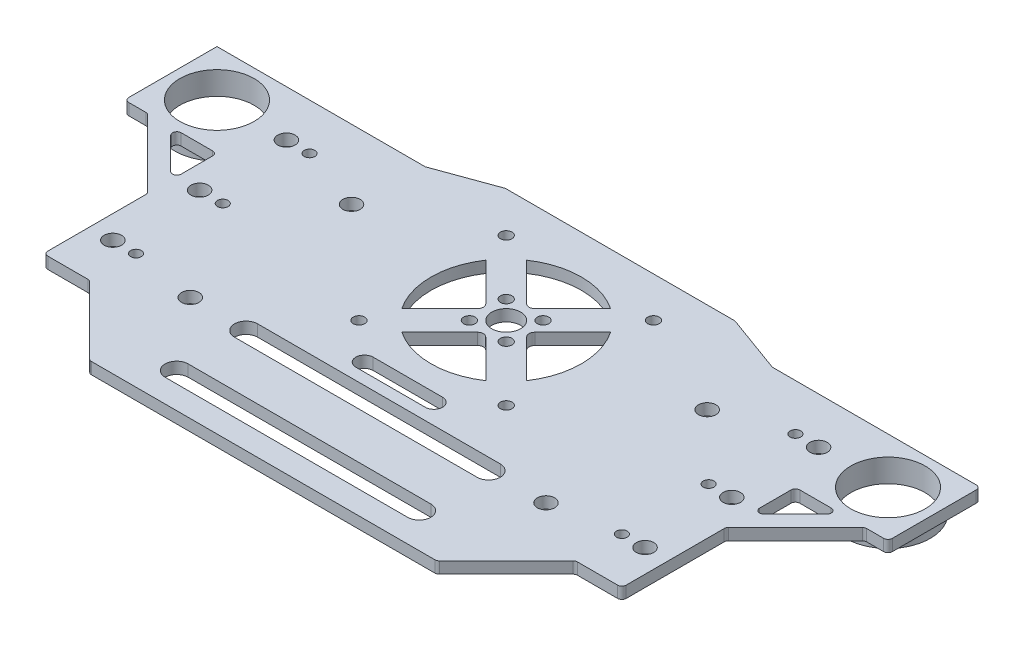
SolidWorks part; units mm, degrees
ref_plane "前视基准面" through (0, 0, 0) normal (0, 0, 1) x (1, 0, 0)
ref_plane "上视基准面" through (0, 0, 0) normal (0, 1, 0) x (1, 0, 0)
ref_plane "右视基准面" through (0, 0, 0) normal (1, 0, 0) x (0, 0, -1)
other "Configuration Table"
sketch "草图1" plane through (0, 0, 0) normal (0, 1, 0) x (1, 0, 0)
  line L0 (-50, 23) -> (50, 23)
  line L1 (50, 23) -> (50, -23)
  line L2 (50, -23) -> (-50, -23)
  line L3 (-50, -23) -> (-50, 23)
  line L5 (0, 23) -> (0, -23) construction
  line L6 (3.182, 10.182) -> (-3.182, 3.818) construction
  line L7 (7.253, 17.7886) -> (-10.7886, -0.253) construction
  line L8 (10.7886, 14.253) -> (-7.253, -3.7886) construction
  line L9 (10.7886, -0.253) -> (-7.253, 17.7886) construction
  line L10 (7.253, -3.7886) -> (-10.7886, 14.253) construction
  line L11 (-7.253, -3.7886) -> (10.7886, 14.253) construction
  line L12 (-10.7886, -0.253) -> (7.253, 17.7886) construction
  line L13 (-10.7886, 14.253) -> (7.253, -3.7886) construction
  line L14 (-7.253, 17.7886) -> (10.7886, -0.253) construction
  line L15 (10.7886, -0.253) -> (4.2426, 6.2929)
  line L16 (4.2426, 7.7071) -> (10.7886, 14.253)
  line L17 (7.253, 17.7886) -> (0.7071, 11.2426)
  line L18 (-0.7071, 11.2426) -> (-7.253, 17.7886)
  line L19 (-10.7886, 14.253) -> (-4.2426, 7.7071)
  line L20 (-4.2426, 6.2929) -> (-10.7886, -0.253)
  line L21 (-7.253, -3.7886) -> (-0.7071, 2.7574)
  line L22 (0.7071, 2.7574) -> (7.253, -3.7886)
  line L23 (-30, 23) -> (-19.848, 26.695)
  line L24 (-19.848, 26.695) -> (0, 26.695)
  line L25 (30, 23) -> (19.848, 26.695)
  line L26 (19.848, 26.695) -> (0, 26.695)
  line L27 (-50, 23) -> (-66, 23)
  line L28 (-66, 23) -> (-66, 7)
  line L29 (-66, 7) -> (-50, 7)
  line L30 (-50, 7) -> (-50, 23)
  line L31 (-58, 7) -> (-50, -1)
  line L32 (-62, 7) -> (-50, -5)
  line L33 (-50, -1) -> (-50, -5)
  line L34 (-58, 7) -> (-62, 7)
  line L35 (58, 7) -> (62, 7)
  line L36 (50, -1) -> (50, -5)
  line L37 (62, 7) -> (50, -5)
  line L38 (58, 7) -> (50, -1)
  line L39 (50, 7) -> (50, 23)
  line L40 (66, 7) -> (50, 7)
  line L41 (66, 23) -> (66, 7)
  line L42 (50, 23) -> (66, 23)
  line L43 (-42, -23) -> (-30, -35)
  line L44 (-30, -35) -> (30, -35)
  line L45 (42, -23) -> (30, -35)
  line L46 (-42, -23) -> (42, -23)
  line L47 (-46, 23) -> (-46, -23) construction
  line L48 (-50, 0) -> (50, 0) construction
  line L49 (-6, -11.5) -> (6, -11.5) construction
  line L50 (-6, -10) -> (6, -10)
  line L51 (-20.9696, -17) -> (20.9696, -17) construction
  line L52 (-20.9696, -15) -> (20.9696, -15)
  line L53 (-20.9696, -19) -> (20.9696, -19)
  line L54 (-20.9696, -29) -> (20.9696, -29) construction
  line L55 (-20.9696, -27) -> (20.9696, -27)
  line L56 (-20.9696, -31) -> (20.9696, -31)
  line L57 (-6, -13) -> (6, -13)
  line L58 (-42, 15) -> (-42, 14.075) construction
  circle A0 centre (0, 7) radius 2.5
  circle A1 centre (3.182, 10.182) radius 1
  circle A2 centre (3.182, 3.818) radius 1
  circle A3 centre (-3.182, 3.818) radius 1
  circle A4 centre (-3.182, 10.182) radius 1
  circle A5 centre (0, 7) radius 13
  circle A6 centre (12.7279, 19.7279) radius 1
  circle A7 centre (12.7279, -5.7279) radius 1
  circle A8 centre (-12.7279, -5.7279) radius 1
  circle A9 centre (-12.7279, 19.7279) radius 1
  arc A10 (-0.7071, 2.7574) -> (0.7071, 2.7574) centre (0, 2.0503) cw
  arc A11 (-4.2426, 7.7071) -> (-4.2426, 6.2929) centre (-4.9497, 7) cw
  arc A12 (0.7071, 11.2426) -> (-0.7071, 11.2426) centre (0, 11.9497) cw
  arc A13 (4.2426, 6.2929) -> (4.2426, 7.7071) centre (4.9497, 7) cw
  circle A15 centre (-58, 15) radius 6.425
  circle A16 centre (58, 15) radius 6.425
  circle A17 centre (-46, 15) radius 1.5
  circle A18 centre (-46, 0) radius 1.5
  circle A19 centre (-46, -15) radius 1.5
  circle A20 centre (46, -15) radius 1.5
  circle A21 centre (46, 0) radius 1.5
  circle A22 centre (46, 15) radius 1.5
  circle A23 centre (30.7465, 11) radius 1.5
  circle A26 centre (-30.7465, 11) radius 1.5
  circle A27 centre (0, 7) radius 15
  arc A29 (-20.9696, -15) -> (-20.9696, -19) centre (-20.9696, -17) ccw
  arc A30 (20.9696, -19) -> (20.9696, -15) centre (20.9696, -17) ccw
  arc A31 (-20.9696, -27) -> (-20.9696, -31) centre (-20.9696, -29) ccw
  arc A32 (20.9696, -31) -> (20.9696, -27) centre (20.9696, -29) ccw
  arc A33 (-6, -10) -> (-6, -13) centre (-6, -11.5) ccw
  arc A34 (6, -13) -> (6, -10) centre (6, -11.5) ccw
  circle A35 centre (-42, 15) radius 0.925
  circle A36 centre (-42, 0) radius 0.925
  circle A37 centre (-42, -15) radius 0.925
  circle A38 centre (42, -15) radius 0.925
  circle A39 centre (42, 0) radius 0.925
  circle A40 centre (42, 15) radius 0.925
  circle A41 centre (30.7465, -16.87) radius 1.5
  circle A42 centre (-30.7465, -16.87) radius 1.5
  point P5 (50, 0)
  point P6 (0, 23)
  point P42 (0, 3.4645)
  point P45 (-3.5355, 7)
  point P48 (0, 10.5355)
  point P51 (3.5355, 7)
  point P64 (-58, 23)
  point P66 (-66, 15)
  point P84 (0, -35)
  point P92 (-50, 0)
  point P111 (0, -11.5)
  point P116 (0, -17)
  point P122 (0, -29)
  dimension "D3" = 5
  dimension "D4" = 2
  dimension "D8" = 26
  dimension "D9" = 2
  dimension "D13" = 1
  dimension "D18" = 16
  dimension "D19" = 16
  dimension "D20" = 12.85
  dimension "D26" = 3
  dimension "D27" = 4
  dimension "D28" = 3
  dimension "D29" = 3
  dimension "D32" = 3
  dimension "D35" = 30
  dimension "D36" = 1.5
  dimension "D44" = 1.85
  dimension "D34" = 3
  dimension "D50" = 3
  dimension "D1" = 100
  dimension "D2" = 46
  dimension "D6" = 9
  dimension "D7" = 45
  dimension "D11" = 18
  dimension "D14" = 16
  dimension "D15" = 20
  dimension "D16" = 20
  dimension "D17" = 3.695
  dimension "D21" = 4
  dimension "D22" = 45
  dimension "D23" = 8
  dimension "D24" = 45
  dimension "D25" = 12
  dimension "D30" = 15
  dimension "D31" = 15
  dimension "D33" = 61.493
  dimension "D37" = 6
  dimension "D38" = 12
  dimension "D39" = 6
  dimension "D40" = 2
  dimension "D41" = 2
  dimension "D42" = 20.9696
  dimension "D43" = 5.5
  dimension "D45" = 4
  dimension "D47" = 46
  dimension "D48" = 27.87
  dimension "D49" = 12
  dimension "D46" = 3
  dimension "D5" = 4
  dimension "D10" = 4
  dimension "D12" = 4
extrude "凸台-拉伸1" add sketch "草图1" along normal blind 2
fillet "圆角1" radius 0.75 19 edges at (-50, 1, 5) (-62, 1, -7) (-42, 1, 23) (-30, 1, 35) (30, 1, 35) (42, 1, 23) (62, 1, -7) (50, 1, 5) (50, 1, 23) (50, 1, -7) (58, 1, -7) (66, 1, -7) (50, 1, 1) (66, 1, -23) (-50, 1, 1) (-58, 1, -7) (-50, 1, -7) (-50, 1, 23) (-66, 1, -7)
sketch "草图2" plane through (0, 2, 0) normal (0, 1, 0) x (1, 0, 0)
  text T0 "M3" font "@Microsoft YaHei UI" height 2
  text T1 "M2" font "@Microsoft YaHei UI" height 2
  text T2 "M3" font "@Microsoft YaHei UI" height 2
sketch "草图3" plane through (0, 0, 0) normal (0, -1, 0) x (1, 0, 0)
  line L0 (0, 0) -> (0, 4.4315) construction
  circle A0 centre (-58, -15) radius 6.425
  circle A1 centre (-58, -15) radius 7.3
  circle A2 centre (58, -15) radius 6.425
  circle A3 centre (58, -15) radius 7.3
  circle A4 centre (-58, -15) radius 6.425 construction
  dimension "D1" = 14.6
extrude "凸台-拉伸2" add sketch "草图3" along normal blind 2
